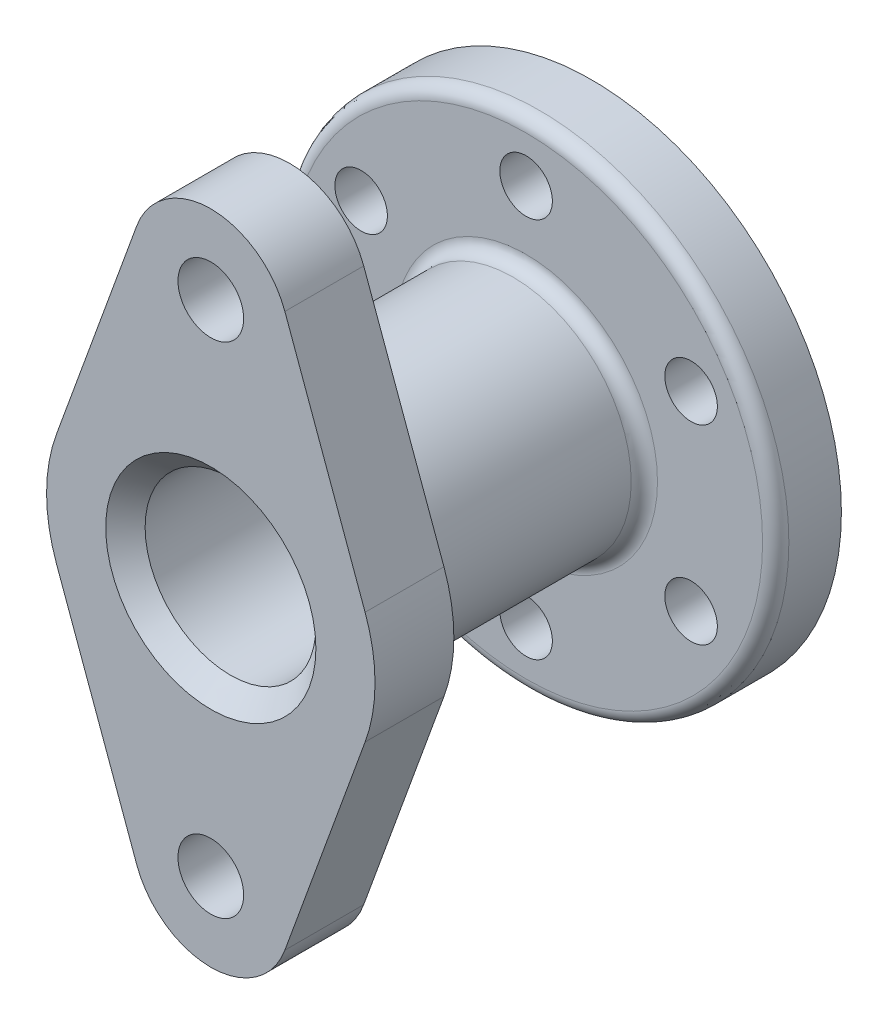
SolidWorks part; units mm, degrees
ref_plane "前基準面" through (0, 0, 0) normal (0, 0, 1) x (1, 0, 0)
ref_plane "上基準面" through (0, 0, 0) normal (0, 1, 0) x (1, 0, 0)
ref_plane "右基準面" through (0, 0, 0) normal (1, 0, 0) x (0, 0, -1)
sketch "草圖1" plane through (0, 0, 0) normal (1, 0, 0) x (0, 0, -1)
  line L0 (0, 0) -> (-68.7174, 0) construction
  line L1 (0, 0) -> (0, 38)
  line L2 (0, 38) -> (-10, 38)
  line L3 (-10, 38) -> (-10, 18)
  line L4 (-10, 18) -> (-58, 18)
  line L5 (-58, 18) -> (-58, 0)
  line L6 (-58, 0) -> (0, 0)
  dimension "D1" = 36
  dimension "D2" = 76
  dimension "D3" = 10
  dimension "D4" = 58
revolve "旋轉1" add sketch "草圖1" angle 360 about L0
sketch "草圖2" plane through (0, 0, 10) normal (0, 0, 1) x (1, 0, 0)
  circle A0 centre (0, 29) radius 4
  circle A1 centre (0, 0) radius 29 construction
  dimension "D1" = 8
  dimension "D2" = 58
extrude "伸長1" cut sketch "草圖2" against normal through all
pattern_circular "環狀複製排列1" count 6 over 360 about axis through (0, 0, 0) along (0, 0, 1) of "伸長1"
sketch "草圖3" plane through (0, 0, 58) normal (0, 0, 1) x (1, 0, 0)
  line L0 (-23.4915, 8.5526) -> (-11.2759, 42.1053)
  line L1 (11.2759, 42.1053) -> (23.4915, 8.5526)
  line L2 (0, 0) -> (40.547, 0) construction
  line L3 (0, 0) -> (0, 38) construction
  line L4 (-23.4915, -8.5526) -> (-11.2759, -42.1053)
  line L5 (11.2759, -42.1053) -> (23.4915, -8.5526)
  circle A0 centre (0, 0) radius 25
  arc A1 (-11.2759, 42.1053) -> (11.2759, 42.1053) centre (0, 38) cw
  circle A2 centre (0, 38) radius 5
  arc A3 (-11.2759, -42.1053) -> (11.2759, -42.1053) centre (0, -38) ccw
  circle A4 centre (0, -38) radius 5
  circle M1 centre (0, 0) radius 18
  dimension "D1" = 50
  dimension "D2" = 10
  dimension "D3" = 12
  dimension "D4" = 76
extrude "伸長2" add sketch "草圖3" against normal blind 12 contours A1 L0 A0 L1 A2 | A0 M1 | L4 A3 L5 A0 A4
sketch "草圖4" plane through (0, 0, 0) normal (1, 0, 0) x (0, 0, -1)
  line L0 (0, 0) -> (-65.5519, 0) construction
  line L1 (0, -38) -> (0, 38) construction
  line L2 (-58, 0) -> (-58, 13)
  line L3 (-58, 8.5526) -> (-58, -8.5526) construction
  line L4 (-58, 42.1053) -> (-58, 8.5526) construction
  line L5 (-58, 13) -> (-33, 13)
  line L6 (-33, 13) -> (-33, 10)
  line L7 (-33, 10) -> (0, 10)
  line L8 (0, 10) -> (0, 0)
  line L9 (0, 0) -> (-58, 0)
  dimension "D1" = 20
  dimension "D2" = 26
  dimension "D3" = 25
revolve "除料-旋轉1" cut sketch "草圖4" angle 360 about L0
chamfer "導角1" distance 3 angle 45 1 edges at (-13, 0, 58)
fillet "圓角1" radius 2 3 edges at (18, 0, 46) (-18, 0, 10) (-38, 0, 10)
